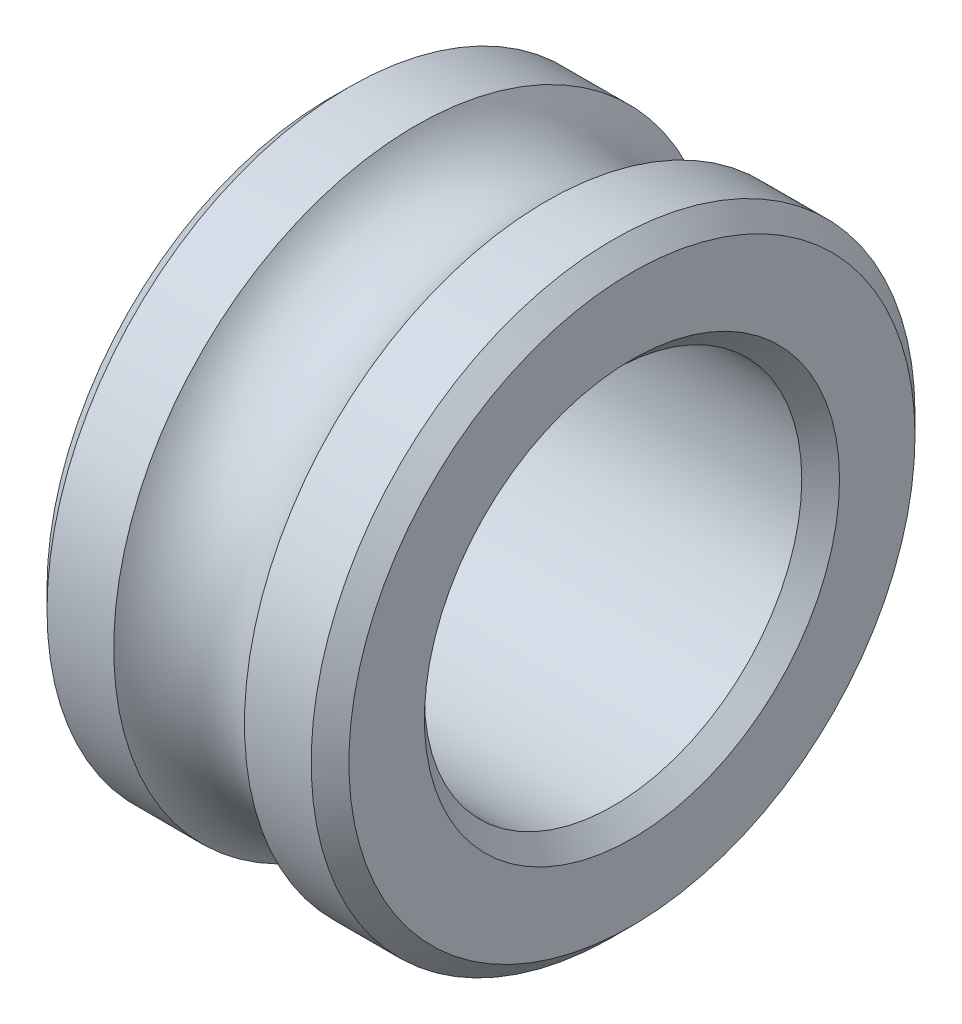
SolidWorks part; units mm, degrees
ref_plane "Ön Düzlem" through (0, 0, 0) normal (0, 0, 1) x (1, 0, 0)
ref_plane "Üst Düzlem" through (0, 0, 0) normal (0, 1, 0) x (1, 0, 0)
ref_plane "Sağ Düzlem" through (0, 0, 0) normal (1, 0, 0) x (0, 0, -1)
sketch "Çizim1" plane through (0, 0, 0) normal (0, 0, 1) x (1, 0, 0)
  line L0 (0, 0) -> (-12.623, 0) construction
  line L1 (-0.524, 5) -> (-8.524, 5)
  line L2 (-8.524, 5) -> (-8.524, 8)
  line L3 (-8.524, 8) -> (-6.256, 8)
  line L4 (-2.7919, 8) -> (-0.524, 8)
  line L5 (-0.524, 8) -> (-0.524, 5)
  arc A0 (-6.256, 8) -> (-2.7919, 8) centre (-4.524, 9) ccw
  point P9 (-2.619, 8)
  dimension "D5" = 2
  dimension "D1" = 10
  dimension "D2" = 8
  dimension "D3" = 3
  dimension "D4" = 3
  dimension "D6" = 4
revolve "Döndür1" add sketch "Çizim1" angle 360 about L0
chamfer "Pah1" distance 0.5 angle 45 4 edges at (-8.524, 0, -8) (-0.524, 0, -8) (-8.524, 0, -5) (-0.524, 0, -5)
